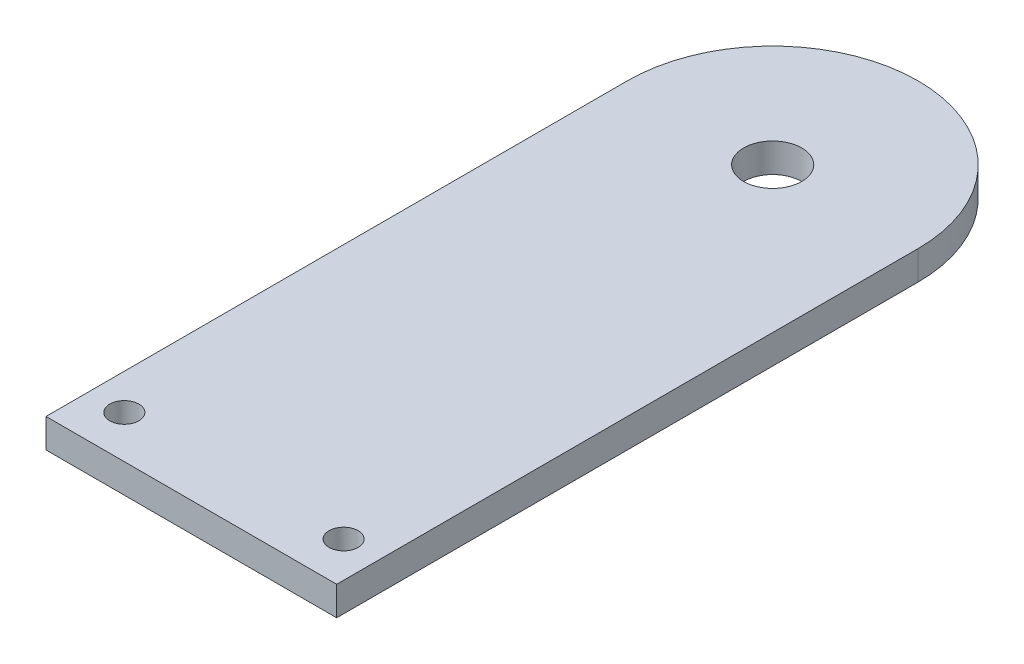
SolidWorks part; units mm, degrees
ref_plane "Front Plane" through (0, 0, 0) normal (0, 0, 1) x (1, 0, 0)
ref_plane "Top Plane" through (0, 0, 0) normal (0, 1, 0) x (1, 0, 0)
ref_plane "Right Plane" through (0, 0, 0) normal (1, 0, 0) x (0, 0, -1)
sketch "Sketch1" plane through (0, 0, 0) normal (0, 1, 0) x (1, 0, 0)
  line L0 (0, 0) -> (50, 0)
  line L1 (50, 0) -> (50, 100)
  line L3 (0, 100) -> (0, 0)
  arc A0 (50, 100) -> (0, 100) centre (25, 100) ccw
  circle A1 centre (25, 100) radius 5
  circle A2 centre (6.1401, 7.3311) radius 2.5
  circle A3 centre (43.8599, 7.3311) radius 2.5
  dimension "D1" = 100
  dimension "D2" = 100
  dimension "D3" = 50
extrude "Boss-Extrude1" add sketch "Sketch1" along normal blind 5
